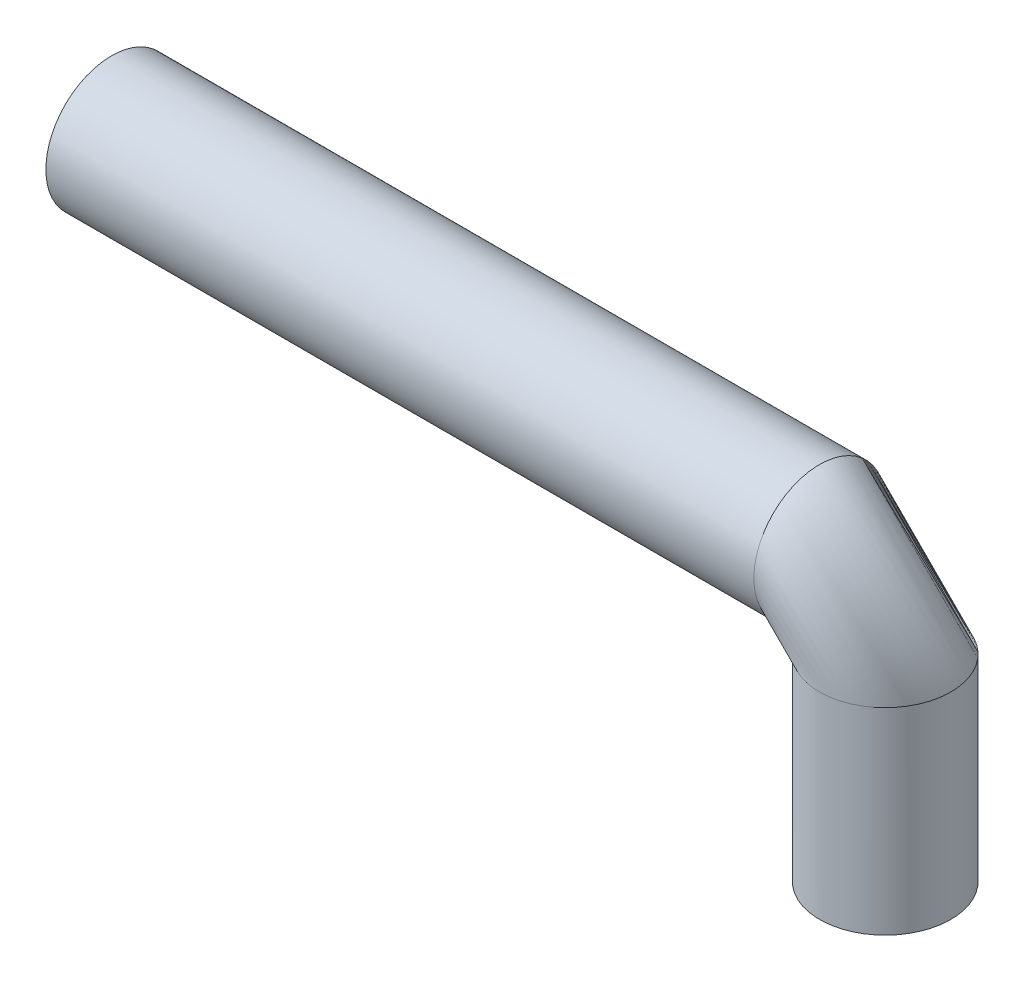
SolidWorks part; units mm, degrees
material "1023 Carbon Steel Sheet (SS)"
ref_plane "Front Plane" through (0, 0, 0) normal (0, 0, 1) x (1, 0, 0)
ref_plane "Top Plane" through (0, 0, 0) normal (0, 1, 0) x (1, 0, 0)
ref_plane "Right Plane" through (0, 0, 0) normal (1, 0, 0) x (0, 0, -1)
sketch "Sketch2" plane through (0, 0, 0) normal (0, 0, 1) x (1, 0, 0)
  line L0 (0, 0) -> (17.1132, 0)
  line L1 (18.7008, -1.5875) -> (18.7008, -6.35)
  arc A0 (17.1132, 0) -> (18.7008, -1.5875) centre (17.1133, -1.5875) cw
  point P6 (18.7008, 0)
  dimension "D3" = 1.5875
  dimension "D1" = 6.35
  dimension "D2" = 18.7008
sketch "Sketch3" plane through (0, 0, 0) normal (1, 0, 0) x (0, 0, -1)
  circle A0 centre (0, 0) radius 1.5875
  dimension "D1" = 3.175
sweep "Sweep1" add profiles "Sketch3" path "Sketch2"
